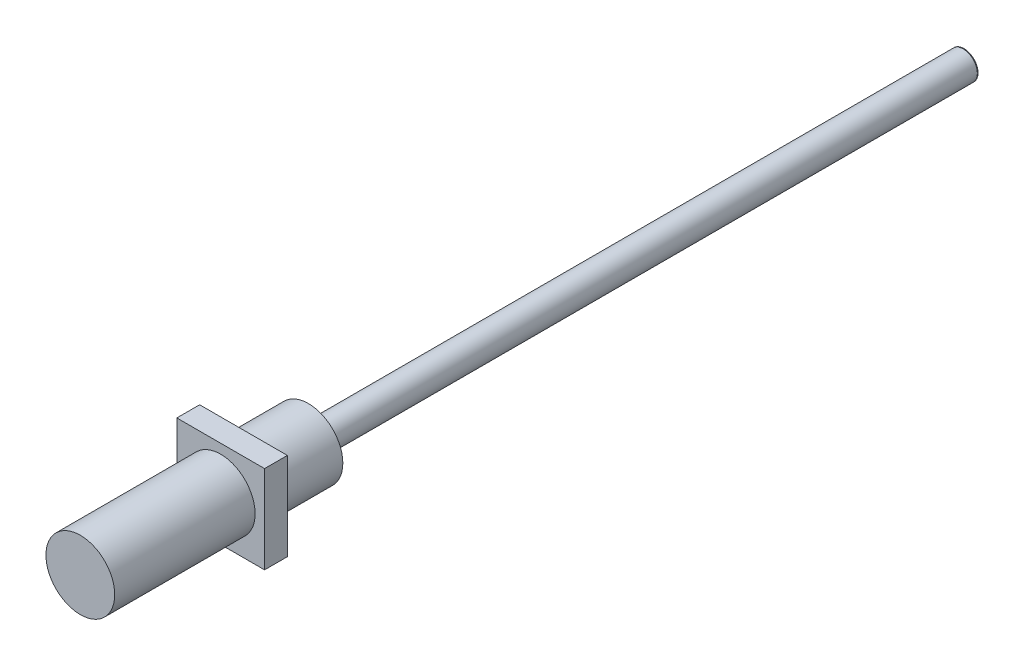
SolidWorks part; units mm, degrees
ref_plane "Front Plane" through (0, 0, 0) normal (0, 0, 1) x (1, 0, 0)
ref_plane "Top Plane" through (0, 0, 0) normal (0, 1, 0) x (1, 0, 0)
ref_plane "Right Plane" through (0, 0, 0) normal (1, 0, 0) x (0, 0, -1)
sketch "Sketch1" plane through (0, 0, 0) normal (0, 0, 1) x (1, 0, 0)
  circle A0 centre (0, 0) radius 1.016
  dimension "D1" = 2.032
extrude "Boss-Extrude1" add sketch "Sketch1" along normal blind 47.371
ref_plane "Plane1" through (0, 0, 47.371) normal (0, 0, 1) x (1, 0, 0)
ref_plane "Plane2" through (0, 0, 0) normal (0, 0, -1) x (-1, 0, 0)
sketch "Sketch2" plane through (0, 0, 0) normal (0, 0, -1) x (-1, 0, 0)
  circle A0 centre (0, 0) radius 1.016
  dimension "D1" = 2.032
extrude "Boss-Extrude2" add sketch "Sketch2" along normal blind 0.0254
ref_plane "Plane3" through (0, 0, -0.0254) normal (0, 0, -1) x (-1, 0, 0)
sketch "Sketch3" plane through (0, 0, -0.0254) normal (0, 0, -1) x (-1, 0, 0)
  line L1 (-0.635, 0.635) -> (0.635, 0.635)
  line L2 (-0.635, 0.635) -> (-0.635, -0.635)
  line L3 (-0.635, -0.635) -> (0.635, -0.635)
  line L4 (0.635, 0.635) -> (0.635, -0.635)
  line L5 (-0.635, 0.635) -> (0.635, -0.635) construction
  line L6 (-0.635, -0.635) -> (0.635, 0.635) construction
  point P0 (0, 0)
  dimension "D1" = 1.27
  dimension "D2" = 1.27
extrude "Boss-Extrude3" add sketch "Sketch3" along normal blind 0.0254
ref_plane "Plane4" through (0, 0, -0.0508) normal (0, 0, -1) x (-1, 0, 0)
sketch "Sketch4" plane through (0, 0, -0.0508) normal (0, 0, -1) x (-1, 0, 0)
  circle A0 centre (0, 0) radius 1.016
  dimension "D1" = 2.032
extrude "Boss-Extrude4" add sketch "Sketch4" along normal blind 0.0254
sketch "Sketch5" plane through (0, 0, 47.371) normal (0, 0, 1) x (1, 0, 0)
  circle A0 centre (0, 0) radius 2.4892
  dimension "D1" = 4.9784
extrude "Boss-Extrude5" add sketch "Sketch5" along normal blind 4.699
ref_plane "Plane5" through (0, 0, 52.07) normal (0, 0, 1) x (1, 0, 0)
sketch "Sketch6" plane through (0, 0, 52.07) normal (0, 0, 1) x (1, 0, 0)
  line L1 (-3.175, 3.175) -> (3.175, 3.175)
  line L2 (-3.175, 3.175) -> (-3.175, -3.175)
  line L3 (-3.175, -3.175) -> (3.175, -3.175)
  line L4 (3.175, 3.175) -> (3.175, -3.175)
  line L5 (-3.175, 3.175) -> (3.175, -3.175) construction
  line L6 (-3.175, -3.175) -> (3.175, 3.175) construction
  point P0 (0, 0)
  dimension "D1" = 6.35
  dimension "D2" = 6.35
extrude "Boss-Extrude6" add sketch "Sketch6" along normal blind 1.651
ref_plane "Plane6" through (0, 0, 53.721) normal (0, 0, 1) x (1, 0, 0)
sketch "Sketch7" plane through (0, 0, 53.721) normal (0, 0, 1) x (1, 0, 0)
  circle A0 centre (0, 0) radius 2.4892
  dimension "D1" = 4.9784
extrude "Boss-Extrude7" add sketch "Sketch7" along normal blind 10.16
ref_plane "center plane" through (0, 0, 31.9024) normal (0, 0, -1) x (-1, 0, 0)
